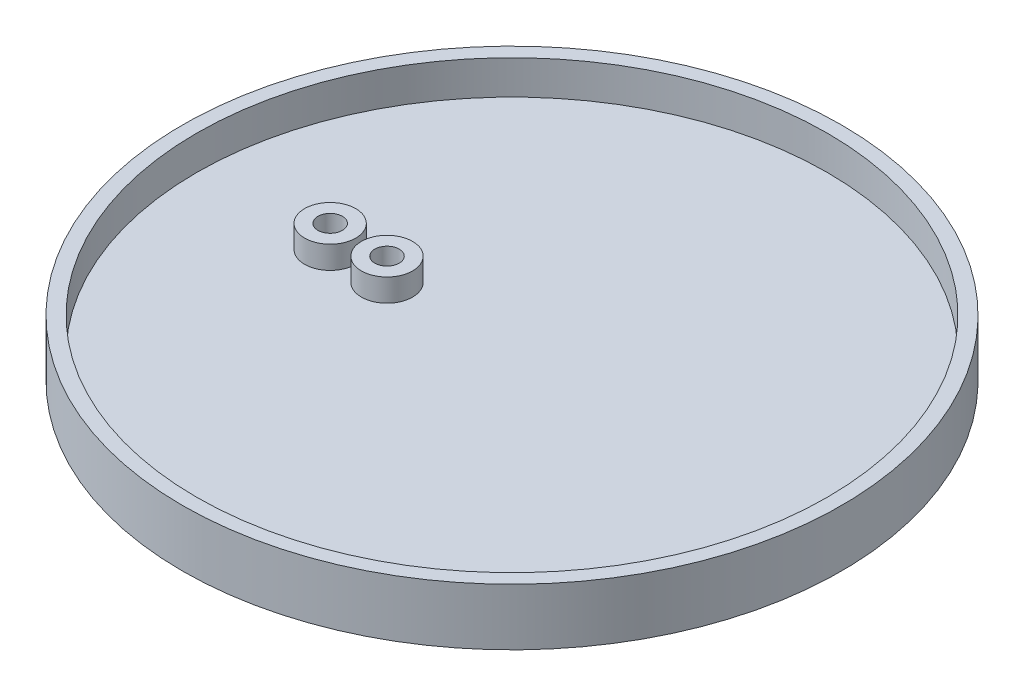
SolidWorks part; units mm, degrees
ref_plane "前视基准面" through (0, 0, 0) normal (0, 0, 1) x (1, 0, 0)
ref_plane "上视基准面" through (0, 0, 0) normal (0, 1, 0) x (1, 0, 0)
ref_plane "右视基准面" through (0, 0, 0) normal (1, 0, 0) x (0, 0, -1)
other "Configuration Table"
sketch "草图1" plane through (0, 0, 0) normal (0, 1, 0) x (1, 0, 0)
  circle A0 centre (-22, 0) radius 4.5
extrude "Moving_post_A" add sketch "草图1" along normal blind 8
sketch "草图2" plane through (0, 0, 0) normal (0, 1, 0) x (1, 0, 0)
  circle A0 centre (0, 0) radius 58
extrude "Cup_plate_D116_T4" add sketch "草图2" along normal blind 4
sketch "草图3" plane through (0, 0, 0) normal (0, 1, 0) x (1, 0, 0)
  circle A0 centre (-32, 0) radius 4.5
extrude "Moving_post_B" add sketch "草图3" along normal blind 8
sketch "草图4" plane through (0, 0, 0) normal (0, 1, 0) x (1, 0, 0)
  circle A0 centre (0, 0) radius 58
  circle A1 centre (0, 0) radius 55.5
extrude "Drip_skirt_OD116_ID111_H10" add sketch "草图4" along normal blind 10
sketch "草图5" plane through (0, 0, 0) normal (0, 1, 0) x (1, 0, 0)
  circle A0 centre (-22, 0) radius 2.15
  circle A1 centre (-32, 0) radius 2.15
extrude "M4_moving_mount_clearance" cut sketch "草图5" along normal blind 8
